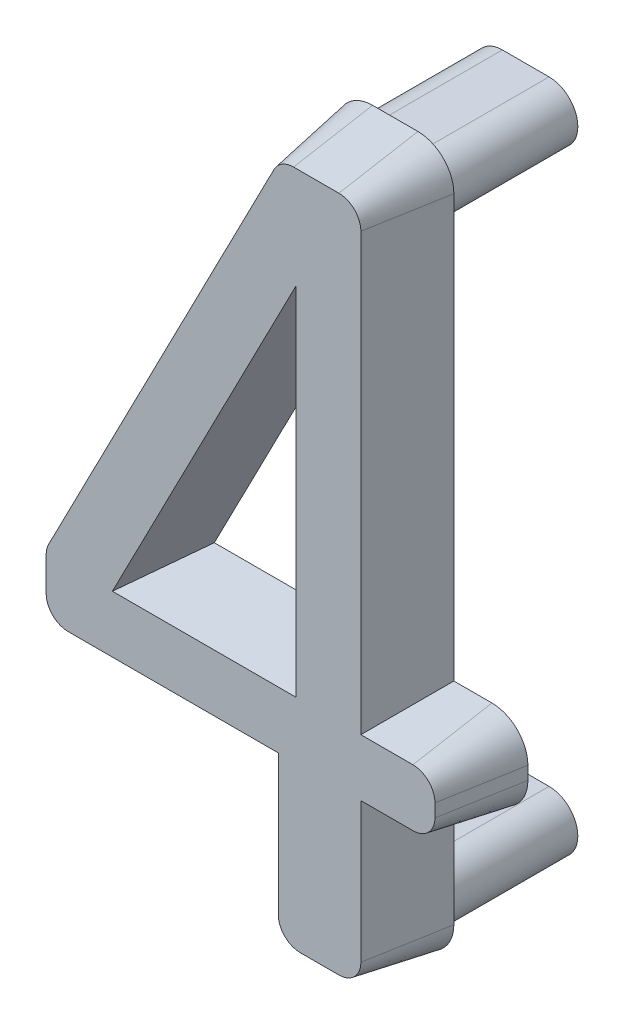
SolidWorks part; units mm, degrees
ref_plane "Plan de face" through (0, 0, 0) normal (0, 0, 1) x (1, 0, 0)
ref_plane "Plan de dessus" through (0, 0, 0) normal (0, 1, 0) x (1, 0, 0)
ref_plane "Plan de droite" through (0, 0, 0) normal (1, 0, 0) x (0, 0, -1)
sketch "Esquisse2" plane through (0, 0, 0) normal (0, 0, 1) x (1, 0, 0)
  line L0 (0, 0) -> (87.7731, 0) construction
  line L106 (59.3334, 1.1702) -> (59.3334, 2.6896)
  line L107 (59.3334, 2.6896) -> (59.3334, 4.6799)
  line L108 (59.3334, 4.6799) -> (53.874, 4.6799)
  line L109 (52.874, 5.6799) -> (52.874, 6.6201)
  line L110 (52.9851, 7.0783) -> (59.2576, 19.2471)
  line L111 (60.1465, 19.7889) -> (61.4077, 19.7889)
  line L112 (62.4077, 18.7889) -> (62.4077, 7.0439)
  line L113 (62.4077, 7.0439) -> (63.4684, 7.0439)
  line L114 (64.4684, 6.0439) -> (64.4684, 5.6799)
  line L115 (63.4684, 4.6799) -> (62.4077, 4.6799)
  line L116 (62.4077, 4.6799) -> (62.4077, 1.1702)
  line L117 (61.4077, 0.1702) -> (60.3334, 0.1702)
  line L118 (59.8235, 7.0439) -> (59.8235, 14.9638)
  line L119 (59.8235, 14.9638) -> (55.7411, 7.0439)
  line L120 (55.7411, 7.0439) -> (59.8235, 7.0439)
  arc A13 (59.3334, 1.1702) -> (60.3334, 0.1702) centre (60.3334, 1.1702) ccw
  arc A14 (62.4077, 1.1702) -> (61.4077, 0.1702) centre (61.4077, 1.1702) cw
  arc A15 (64.4684, 5.6799) -> (63.4684, 4.6799) centre (63.4684, 5.6799) cw
  arc A16 (63.4684, 7.0439) -> (64.4684, 6.0439) centre (63.4684, 6.0439) cw
  arc A17 (61.4077, 19.7889) -> (62.4077, 18.7889) centre (61.4077, 18.7889) cw
  arc A18 (59.2576, 19.2471) -> (60.1465, 19.7889) centre (60.1465, 18.7889) cw
  arc A19 (52.874, 6.6201) -> (52.9851, 7.0783) centre (53.874, 6.6201) cw
  arc A20 (53.874, 4.6799) -> (52.874, 5.6799) centre (53.874, 5.6799) cw
  dimension "D3" = 1
extrude "Boss.-Extru.3" add sketch "Esquisse2" along normal blind 2.2 draft 10
sketch "Esquisse3" plane through (0, 0, 0) normal (0, 0, 1) x (1, 0, 0)
  line L7 (61.4077, 19.7889) -> (60.1465, 19.7889) construction
  line L9 (62.4077, 7.0439) -> (62.4077, 18.7889) construction
  line L48 (-79.7948, 19.7889) -> (6.415, 19.7889) construction
  line L49 (-79.7948, 0.1702) -> (6.415, 0.1702) construction
  line L53 (-79.7948, 19.7889) -> (-79.7948, 0.1702) construction
  line L54 (-79.7948, 9.9795) -> (6.415, 9.9795) construction
  line L55 (-79.7948, 18.5295) -> (6.415, 18.5295) construction
  line L56 (-79.7948, 1.4295) -> (6.415, 1.4295) construction
  line L78 (60.1577, 18.5295) -> (61.4577, 18.5295) construction
  line L79 (60.1577, 19.3295) -> (61.4577, 19.3295)
  line L80 (60.1577, 17.7295) -> (61.4577, 17.7295)
  line L81 (60.1577, 1.4295) -> (61.4577, 1.4295) construction
  line L82 (60.1577, 2.2295) -> (61.4577, 2.2295)
  line L83 (60.1577, 0.6295) -> (61.4577, 0.6295)
  arc A40 (60.1577, 19.3295) -> (60.1577, 17.7295) centre (60.1577, 18.5295) ccw
  arc A41 (61.4577, 17.7295) -> (61.4577, 19.3295) centre (61.4577, 18.5295) ccw
  arc A42 (60.1577, 2.2295) -> (60.1577, 0.6295) centre (60.1577, 1.4295) ccw
  arc A43 (61.4577, 0.6295) -> (61.4577, 2.2295) centre (61.4577, 1.4295) ccw
  point P1 (9.5646, 19.3295)
  point P2 (0, 0)
  point P3 (0, 0)
  point P168 (60.8077, 18.5295)
  point P175 (60.8077, 1.4295)
  dimension "D1" = 1.6
  dimension "D4" = 1.6
  dimension "D5" = 19.6187
  dimension "D7" = 1.6
  dimension "D21" = 19.6187
  dimension "D22" = 17.1
  dimension "D32" = 1.3
  dimension "D35" = 1.3
extrude "Boss.-Extru.4" add sketch "Esquisse3" against normal blind 3.6
